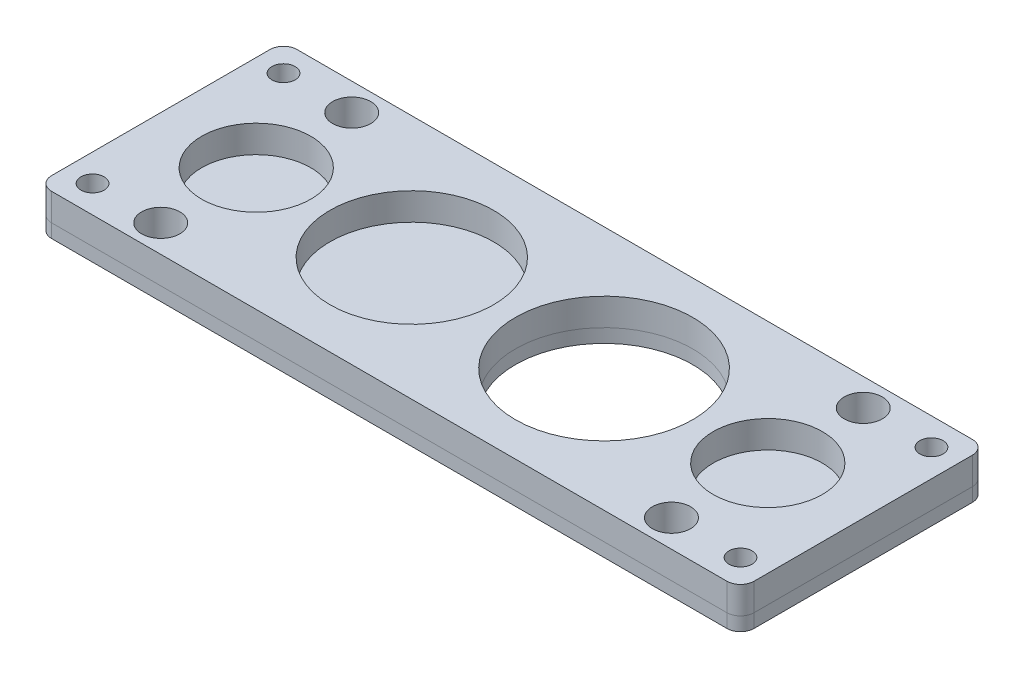
SolidWorks part; units mm, degrees
ref_plane "Front Plane" through (0, 0, 0) normal (0, 0, 1) x (1, 0, 0)
ref_plane "Top Plane" through (0, 0, 0) normal (0, 1, 0) x (1, 0, 0)
ref_plane "Right Plane" through (0, 0, 0) normal (1, 0, 0) x (0, 0, -1)
sketch "Sketch2" plane through (0, 0, 0) normal (0, 1, 0) x (1, 0, 0)
  line L3 (-50.1915, 20.4286) -> (52.8085, 20.4286)
  line L4 (-50.1915, 20.4286) -> (-50.1915, -15.5714)
  line L5 (-50.1915, -15.5714) -> (52.8085, -15.5714)
  line L6 (52.8085, 20.4286) -> (52.8085, -15.5714)
  circle A0 centre (-46.1915, 16.4286) radius 1.7
  circle A1 centre (-46.1915, -11.5714) radius 1.7
  circle A2 centre (48.8085, 16.4286) radius 1.7
  circle A3 centre (48.8085, -11.5714) radius 1.7
  circle A6 centre (14.8085, 2.4286) radius 13
  circle A7 centre (-36.1915, 16.4286) radius 1.7
  circle A8 centre (-36.1915, -11.5714) radius 1.7
  circle A9 centre (38.8085, 16.4286) radius 1.7
  circle A10 centre (38.6904, -11.5714) radius 1.7
  dimension "D1" = 95
  dimension "D3" = 95
  dimension "D4" = 4
  dimension "D6" = 4
  dimension "D9" = 34
  dimension "D11" = 75
  dimension "D2" = 28
  dimension "D5" = 4
  dimension "D7" = 4
  dimension "D8" = 4
  dimension "D10" = 14
  dimension "D12" = 28
  dimension "D13" = 28
  dimension "D14" = 10
extrude "Boss-Extrude1" add sketch "Sketch2" along normal blind 2
fillet "Fillet1" radius 2 4 edges at (52.8085, 1, -20.4286) (52.8085, 1, 15.5714) (-50.1915, 1, -20.4286) (-50.1915, 1, 15.5714)
sketch "Sketch6" plane through (0, 2, 0) normal (0, 1, 0) x (1, 0, 0)
  line L3 (-50.1915, 20.4286) -> (52.8085, 20.4286)
  line L4 (-50.1915, 20.4286) -> (-50.1915, -15.5714)
  line L5 (-50.1915, -15.5714) -> (52.8085, -15.5714)
  line L6 (52.8085, 20.4286) -> (52.8085, -15.5714)
  circle A0 centre (-46.1915, 16.4286) radius 1.7
  circle A1 centre (-46.1915, -11.5714) radius 1.7
  circle A2 centre (48.8085, 16.4286) radius 1.7
  circle A3 centre (48.8085, -11.5714) radius 1.7
  circle A6 centre (14.8085, 2.4286) radius 13
  circle A7 centre (-36.1915, 16.4286) radius 2.8
  circle A8 centre (-36.1915, -11.5714) radius 2.8
  circle A9 centre (38.8085, 16.4286) radius 2.8
  circle A10 centre (38.6904, -11.5714) radius 2.8
  circle A11 centre (-36.1915, 2.4286) radius 8
  circle A12 centre (-13.3851, 2.4286) radius 12
  circle A13 centre (38.8085, 2.4286) radius 8
  point P28 (0, 0)
  dimension "D1" = 95
  dimension "D3" = 95
  dimension "D4" = 4
  dimension "D6" = 4
  dimension "D9" = 34
  dimension "D11" = 75
  dimension "D2" = 28
  dimension "D5" = 4
  dimension "D7" = 4
  dimension "D8" = 4
  dimension "D10" = 14
  dimension "D12" = 28
  dimension "D13" = 28
  dimension "D14" = 10
extrude "Boss-Extrude3" add sketch "Sketch6" along normal blind 4 separate body
fillet "Fillet2" radius 2 4 edges at (52.8085, 4, -20.4286) (52.8085, 4, 15.5714) (-50.1915, 4, -20.4286) (-50.1915, 4, 15.5714)
